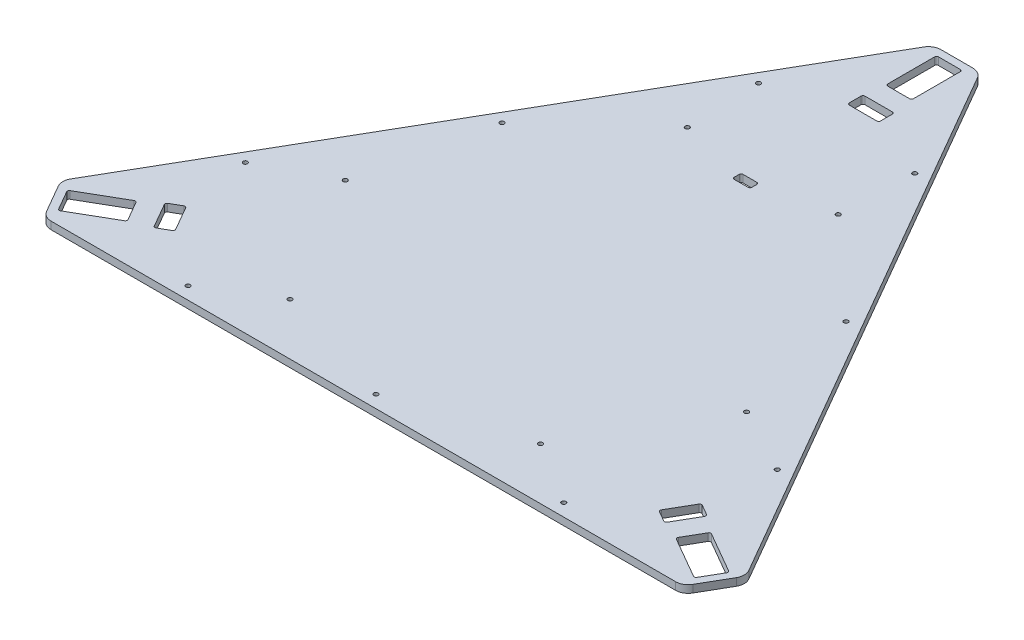
SolidWorks part; units mm, degrees
material "Керамика фарфор"
ref_plane "Спереди" through (0, 0, 0) normal (0, 0, 1) x (1, 0, 0)
ref_plane "Сверху" through (0, 0, 0) normal (0, 1, 0) x (1, 0, 0)
ref_plane "Справа" through (0, 0, 0) normal (1, 0, 0) x (0, 0, -1)
sketch "Эскиз1" plane through (0, 0, 0) normal (0, 1, 0) x (1, 0, 0)
  line L17 (273.664, -136.638) -> (18.5, 305.319)
  line L18 (18.5, 305.319) -> (-18.5, 305.319)
  line L19 (-18.5, 305.319) -> (-273.664, -136.638)
  line L29 (219.0188, -138.2863) -> (254.0929, -158.5363)
  line L30 (-10.25, 299.319) -> (10.25, 299.319)
  line L31 (-273.664, -136.638) -> (-255.164, -168.681)
  line L32 (-255.164, -168.681) -> (255.164, -168.681)
  line L33 (255.164, -168.681) -> (273.664, -136.638)
  line L34 (-264.414, -152.6595) -> (0, 0) construction
  line L35 (0, 0) -> (146.082, 84.3405) construction
  line L36 (264.414, -152.6595) -> (0, 0) construction
  line L37 (0, 0) -> (-146.082, 84.3405) construction
  line L38 (0, 305.319) -> (0, 0) construction
  line L39 (0, 0) -> (0, -168.681) construction
  line L40 (-10.25, 299.319) -> (-10.25, 258.819)
  line L41 (-10.25, 258.819) -> (10.25, 258.819)
  line L42 (10.25, 299.319) -> (10.25, 258.819)
  line L43 (-10.25, 299.319) -> (10.25, 258.819) construction
  line L44 (-10.25, 258.819) -> (10.25, 299.319) construction
  line L45 (219.0188, -138.2863) -> (229.2688, -120.5327)
  line L46 (254.0929, -158.5363) -> (264.3429, -140.7827)
  line L47 (229.2688, -120.5327) -> (264.3429, -140.7827)
  line L48 (219.0188, -138.2863) -> (264.3429, -140.7827) construction
  line L49 (254.0929, -158.5363) -> (229.2688, -120.5327) construction
  line L50 (-229.2688, -120.5327) -> (-264.3429, -140.7827)
  line L51 (-229.2688, -120.5327) -> (-219.0188, -138.2863)
  line L52 (-264.3429, -140.7827) -> (-254.0929, -158.5363)
  line L53 (-219.0188, -138.2863) -> (-254.0929, -158.5363)
  line L54 (-229.2688, -120.5327) -> (-254.0929, -158.5363) construction
  line L55 (-264.3429, -140.7827) -> (-219.0188, -138.2863) construction
  line L56 (216.5374, -110.5842) -> (204.0374, -132.2348)
  line L57 (-12.5, 242.819) -> (12.5, 242.819)
  line L58 (-12.5, 242.819) -> (-12.5, 230.319)
  line L59 (-12.5, 230.319) -> (12.5, 230.319)
  line L60 (12.5, 242.819) -> (12.5, 230.319)
  line L61 (-12.5, 242.819) -> (12.5, 230.319) construction
  line L62 (-12.5, 230.319) -> (12.5, 242.819) construction
  line L63 (216.5374, -110.5842) -> (193.2121, -125.9848) construction
  line L64 (216.5374, -110.5842) -> (205.7121, -104.3342)
  line L65 (205.7121, -104.3342) -> (204.0374, -132.2348) construction
  line L66 (205.7121, -104.3342) -> (193.2121, -125.9848)
  line L67 (204.0374, -132.2348) -> (193.2121, -125.9848)
  line L68 (-204.0374, -132.2348) -> (-216.5374, -110.5842)
  line L69 (-204.0374, -132.2348) -> (-205.7121, -104.3342) construction
  line L70 (-204.0374, -132.2348) -> (-193.2121, -125.9848)
  line L71 (-193.2121, -125.9848) -> (-216.5374, -110.5842) construction
  line L72 (-193.2121, -125.9848) -> (-205.7121, -104.3342)
  line L73 (-216.5374, -110.5842) -> (-205.7121, -104.3342)
  line L75 (-7, 140) -> (7, 140)
  line L76 (-7, 140) -> (-7, 133)
  line L77 (-7, 133) -> (7, 133)
  line L78 (7, 140) -> (7, 133)
  point P3 (0, -168.681)
  point P11 (0, 305.319)
  point P14 (0, 279.069)
  point P20 (0, 236.569)
  point P22 (241.6809, -139.5345)
  point P23 (-241.6809, -139.5345)
  point P47 (0, 0)
  point P49 (0, 133)
  point P50 (-199.4621, -115.1595)
  point P51 (199.4621, -115.1595)
  dimension "D13" = 16
  dimension "D1" = 60
  dimension "D2" = 474
  dimension "D3" = 37
  dimension "D4" = 6
  dimension "D9" = 6
  dimension "D10" = 20.5
  dimension "D11" = 40.5
  dimension "D12" = 6
  dimension "D14" = 12.5
  dimension "D15" = 25
  dimension "D16" = 3
  dimension "D17" = 7
  dimension "D18" = 14
  dimension "D19" = 140
extrude "База" add sketch "Эскиз1" along normal mid plane 6
fillet "Скругление1" radius 10 6 edges at (273.664, 0, 136.638) (255.164, 0, 168.681) (-255.164, 0, 168.681) (-273.664, 0, 136.638) (18.5, 0, -305.319) (-18.5, 0, -305.319)
fillet "Скругление2" radius 1.5 28 edges at (-254.0929, 0, 158.5363) (-219.0188, 0, 138.2863) (-229.2688, 0, 120.5327) (-264.3429, 0, 140.7827) (219.0188, 0, 138.2863) (229.2688, 0, 120.5327) (264.3429, 0, 140.7827) (254.0929, 0, 158.5363) (10.25, 0, -258.819) (-10.25, 0, -258.819) (-10.25, 0, -299.319) (10.25, 0, -299.319) (12.5, 0, -230.319) (-12.5, 0, -230.319) (-12.5, 0, -242.819) (12.5, 0, -242.819) (216.5374, 0, 110.5842) (205.7121, 0, 104.3342) (193.2121, 0, 125.9848) (204.0374, 0, 132.2348) (-204.0374, 0, 132.2348) (-193.2121, 0, 125.9848) (-216.5374, 0, 110.5842) (-205.7121, 0, 104.3342) (-7, 0, -133) (7, 0, -133) (7, 0, -140) (-7, 0, -140)
hole_wizard "Стол 3,5мм" positions "Эскиз2" profile "Эскиз3" hole size "Ø3.5" standard "DIN" end condition through all
sketch "Эскиз2" plane through (0, -3, 0) normal (0, 1, 0) x (1, 0, 0)
  line L0 (-60.25, 150.2554) -> (60.25, 150.2554) construction
  line L1 (60.25, 150.2554) -> (160.25, -22.9497) construction
  line L2 (160.25, -22.9497) -> (100, -127.3057) construction
  line L3 (100, -127.3057) -> (-100, -127.3057) construction
  line L4 (-100, -127.3057) -> (-160.25, -22.9497) construction
  line L5 (-160.25, -22.9497) -> (-60.25, 150.2554) construction
  line L6 (0, 0) -> (0, 150.2554) construction
  line L9 (0, 0) -> (-110.25, 63.6529) construction
  line L12 (0, 0) -> (110.25, 63.6529) construction
  line L15 (0, 0) -> (130.125, -75.1277) construction
  line L18 (0, 0) -> (0, -127.3057) construction
  line L21 (0, 0) -> (-130.125, -75.1277) construction
  point P0 (-100, -127.3057)
  point P3 (-160.25, -22.9497)
  point P6 (100, -127.3057)
  point P9 (160.25, -22.9497)
  point P12 (-60.25, 150.2554)
  point P15 (60.25, 150.2554)
  point P38 (0, 150.2554)
  point P40 (0, -127.3057)
  dimension "D1" = 120.5
  dimension "D2" = 200
sketch "Эскиз3" plane through (-100, -3, 127.3057) normal (1, 0, 0) x (0, 0, -1)
  line L0 (0, 0) -> (0, 6)
  line L1 (0, 6) -> (1.75, 6)
  line L2 (1.75, 6) -> (1.75, 0)
  line L5 (1.75, 0) -> (0, 0)
  line L11 (0, -6.35) -> (0, 107.95) construction
  dimension "Диаметр сквозного отверстия" = 3.5
  dimension "Глубина сквозного отверстия" = 6
hole_wizard "Отверстия 3,5мм" positions "Эскиз4" profile "Эскиз5" hole size "Ø3.5" standard "DIN" end condition through all
sketch "Эскиз4" plane through (0, 3, 0) normal (0, 1, 0) x (1, 0, 0)
  line L0 (-212.4218, -50.5633) -> (-137.4218, 79.3405) construction
  line L1 (-137.4218, 79.3405) -> (-62.4218, 209.2443) construction
  line L4 (62.4218, 209.2443) -> (137.4218, 79.3405) construction
  line L5 (137.4218, 79.3405) -> (212.4218, -50.5633) construction
  line L8 (150, -158.681) -> (0, -158.681) construction
  line L9 (0, -158.681) -> (-150, -158.681) construction
  line L12 (0, -158.681) -> (137.4218, 79.3405) construction
  line L13 (137.4218, 79.3405) -> (-137.4218, 79.3405) construction
  line L14 (-137.4218, 79.3405) -> (0, -158.681) construction
  line L17 (-249.3905, -168.681) -> (249.3905, -168.681) construction
  line L18 (-21.3868, 300.319) -> (-270.7773, -131.638) construction
  point P0 (-137.4218, 79.3405)
  point P2 (-62.4218, 209.2443)
  point P4 (62.4218, 209.2443)
  point P6 (137.4218, 79.3405)
  point P8 (212.4218, -50.5633)
  point P10 (150, -158.681)
  point P12 (0, -158.681)
  point P14 (-150, -158.681)
  point P16 (-212.4218, -50.5633)
  dimension "D1" = 10
  dimension "D2" = 10
  dimension "D3" = 300
  dimension "D4" = 60
  dimension "D5" = 60
sketch "Эскиз5" plane through (-137.4218, 3, -79.3405) normal (1, 0, 0) x (0, 0, 1)
  line L0 (0, 0) -> (0, 6)
  line L1 (0, 6) -> (1.75, 6)
  line L2 (1.75, 6) -> (1.75, 0)
  line L5 (1.75, 0) -> (0, 0)
  line L11 (0, -6.35) -> (0, 107.95) construction
  dimension "Диаметр сквозного отверстия" = 3.5
  dimension "Глубина сквозного отверстия" = 6
